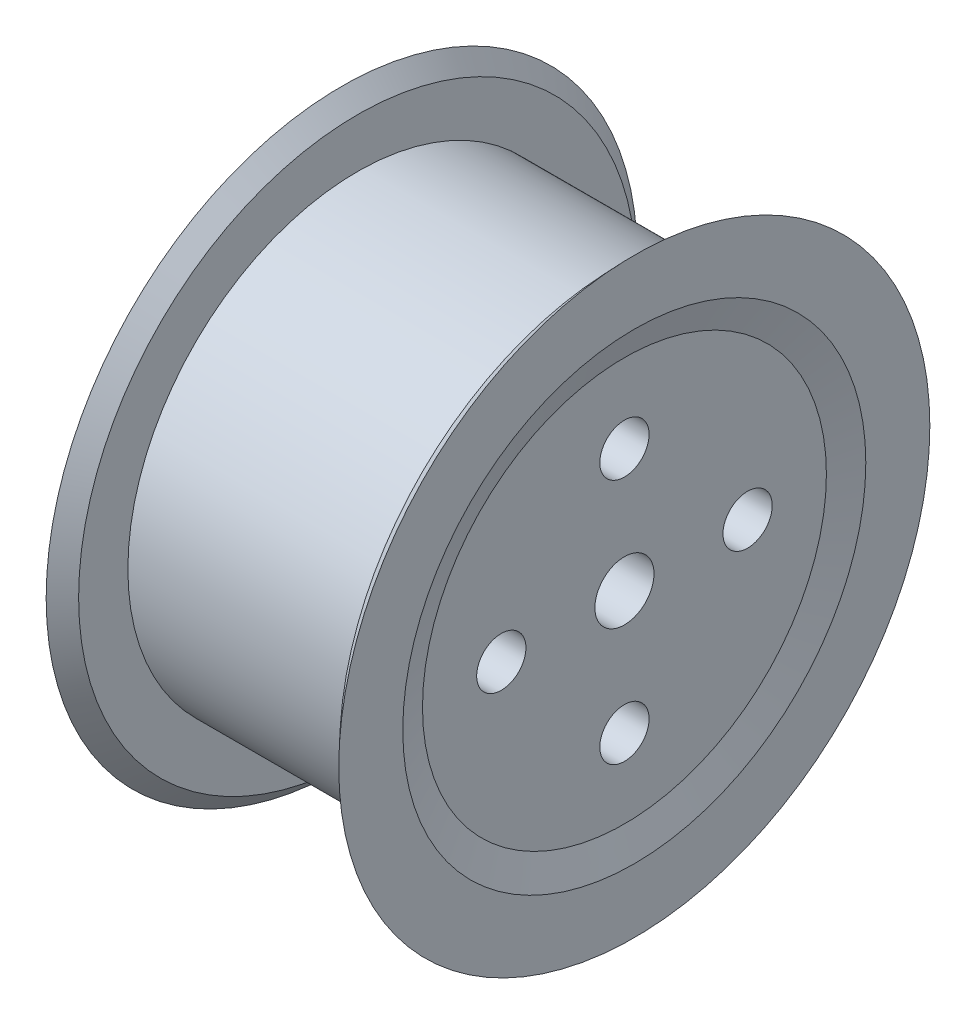
SolidWorks part; units mm, degrees
ref_plane "Front Plane" through (0, 0, 0) normal (0, 0, 1) x (1, 0, 0)
ref_plane "Top Plane" through (0, 0, 0) normal (0, 1, 0) x (1, 0, 0)
ref_plane "Right Plane" through (0, 0, 0) normal (1, 0, 0) x (0, 0, -1)
sketch "Sketch1" plane through (0, 0, 0) normal (0, 0, 1) x (1, 0, 0)
  line L0 (0, 0) -> (65.3409, 0) construction
  line L1 (0, 23.305) -> (28.1, 23.305)
  line L2 (28.1, 23.305) -> (28.1, 28.305)
  line L3 (28.1, 28.305) -> (29.7, 30)
  line L4 (29.7, 30) -> (29.7, 0)
  line L5 (29.7, 0) -> (0, 0)
  line L6 (0, 0) -> (0, 23.305)
  line L7 (0, 17.45) -> (-7.8, 17.45)
  line L8 (-7.8, 17.45) -> (-7.8, 0)
  line L9 (-7.8, 0) -> (0, 0)
  line L10 (0, 23.305) -> (0, 30)
  line L11 (0, 30) -> (1.6, 28.305)
  line L12 (1.6, 28.305) -> (1.6, 23.305)
  line L13 (1.6, 28.305) -> (28.1, 28.305)
  line L14 (0, 30) -> (29.7, 30)
  line L15 (1.6, 28.305) -> (0, 28.305) construction
  line L16 (28.1, 28.305) -> (29.7, 28.305) construction
  line L17 (29.7, 23.5) -> (28.7, 20.5)
  line L18 (28.7, 20.5) -> (28.7, 0)
  line L19 (0, 23.5) -> (1, 20.5)
  line L20 (1, 20.5) -> (1, 17.45)
  line L21 (1, 17.45) -> (0, 17.45)
  line L22 (0, 23.5) -> (29.7, 23.5) construction
  line L23 (1, 20.5) -> (28.7, 20.5) construction
  line L24 (28.7, 20.5) -> (29.7, 20.5) construction
  line L25 (1, 20.5) -> (0, 20.5) construction
  point P11 (-3.9, 17.45)
  dimension "D1" = 26.5
  dimension "D2" = 46.61
  dimension "D3" = 5
  dimension "D4" = 60
  dimension "D5" = 1.6
  dimension "D6" = 34.9
  dimension "D7" = 7.8
  dimension "D8" = 41
  dimension "D9" = 47
  dimension "D10" = 1
revolve "Revolve1" add sketch "Sketch1" angle 360 about L0
sketch "Sketch2" plane through (29.7, 0, 0) normal (1, 0, 0) x (0, 0, -1)
  circle A0 centre (0, 0) radius 12.5 construction
  circle A1 centre (12.5, 0) radius 2.5
  circle A2 centre (0, -12.5) radius 2.5
  circle A3 centre (-12.5, 0) radius 2.5
  circle A4 centre (0, 12.5) radius 2.5
  point P14 (0, 0)
  dimension "D1" = 5
  dimension "D2" = 25
  dimension "D3" = 4
extrude "Cut-Extrude1" cut sketch "Sketch2" against normal through all
hole_wizard "M6 Tapped Hole2" positions "3DSketch2" profile "Sketch4" tap size "M6" standard "ISO"
sketch3d "3DSketch2"
  line L0 (-7.8, 0, -12.5) -> (28.7, 0, -12.5) construction
  line L1 (-7.8, 12.5, 0) -> (28.7, 12.5, 0) construction
  line L2 (-7.8, 0, 12.5) -> (28.7, 0, 12.5) construction
  line L3 (-7.8, -12.5, 0) -> (28.7, -12.5, 0) construction
  point P0 (-7.8, 0, -12.5)
  point P4 (-7.8, 12.5, 0)
  point P8 (-7.8, 0, 12.5)
  point P12 (-7.8, -12.5, 0)
sketch "Sketch4" plane through (-7.8, 0, -12.5) normal (0, 1, 0) x (0, 0, 1)
  line L0 (0, 0) -> (0, 56.5022)
  line L1 (0, 56.5022) -> (2.5, 55)
  line L2 (2.5, 55) -> (2.5, 0.525)
  line L3 (2.5, 0.525) -> (3.025, 0)
  line L5 (3.025, 0) -> (0, 0)
  line L6 (-2.5, 0.525) -> (-3.025, 0) construction
  line L10 (0, 56.5022) -> (-2.5, 55) construction
  line L11 (0, -6.35) -> (0, 107.95) construction
  dimension "Tap Drill Dia." = 5
  dimension "Tap Drill Depth" = 55
  dimension "Near C'Sink Dia." = 6.05
  dimension "Near C'Sink Angle" = 90
  dimension "Drill Angle" = 118
cosmetic thread "Hole Thread1" parameters "D1"=52, "D2"=14.5353
cosmetic thread "Hole Thread2" parameters "D1"=52, "D2"=14.5353
cosmetic thread "Hole Thread3" parameters "D1"=52, "D2"=14.5353
cosmetic thread "Hole Thread4" parameters "D1"=52, "D2"=14.5353
sketch "Sketch5" plane through (28.7, 0, 0) normal (1, 0, 0) x (0, 0, -1)
  circle A0 centre (0, 0) radius 3
  dimension "D1" = 6
extrude "Cut-Extrude2" cut sketch "Sketch5" against normal through all
